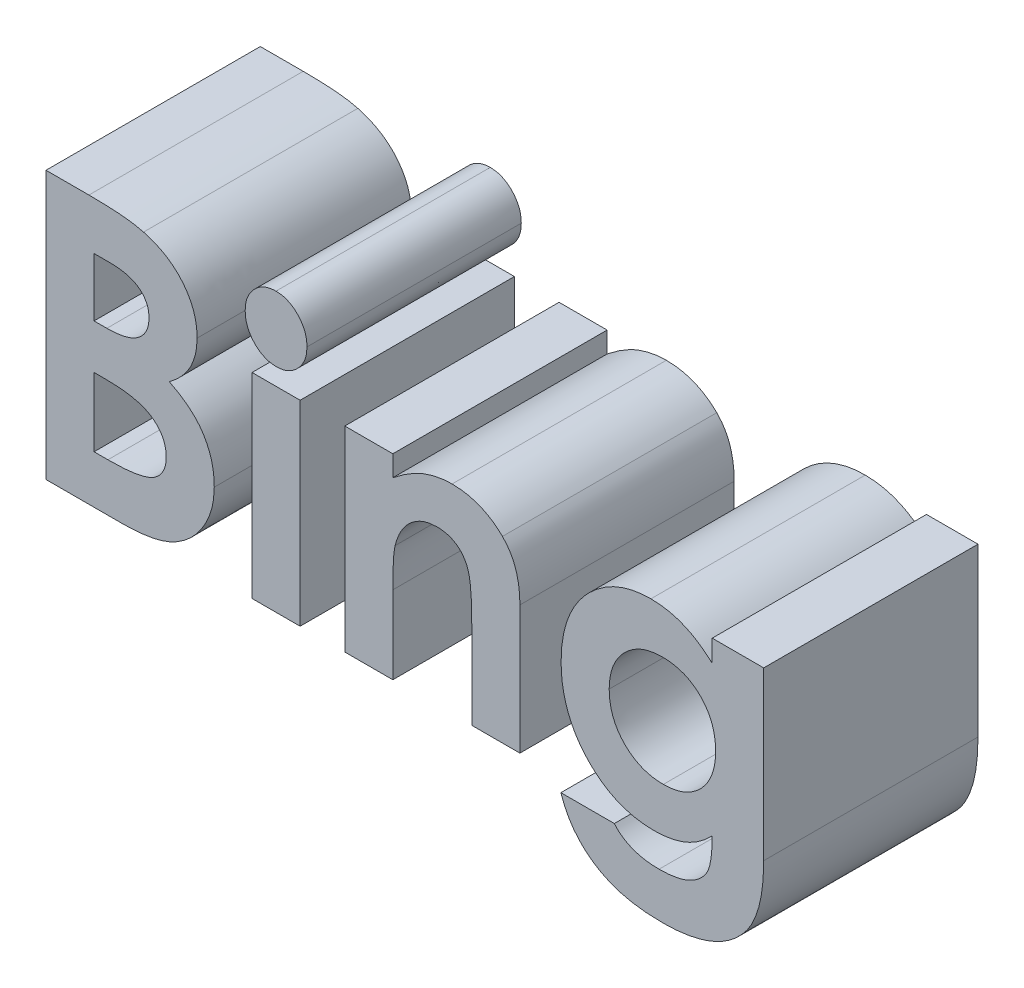
SolidWorks part; units mm, degrees
ref_plane "Front Plane" through (0, 0, 0) normal (0, 0, 1) x (1, 0, 0)
ref_plane "Top Plane" through (0, 0, 0) normal (0, 1, 0) x (1, 0, 0)
ref_plane "Right Plane" through (0, 0, 0) normal (1, 0, 0) x (0, 0, -1)
sketch "Sketch1" plane through (0, 0, 0) normal (0, 0, 1) x (1, 0, 0)
  text T0 "<b>Bing</b>\r\n"
  point P1 (0, 0)
  point P2 (0, 0)
  point P3 (0, 0)
  point P4 (0, 0)
extrude "Boss-Extrude1" add sketch "Sketch1" along normal blind 2.54
